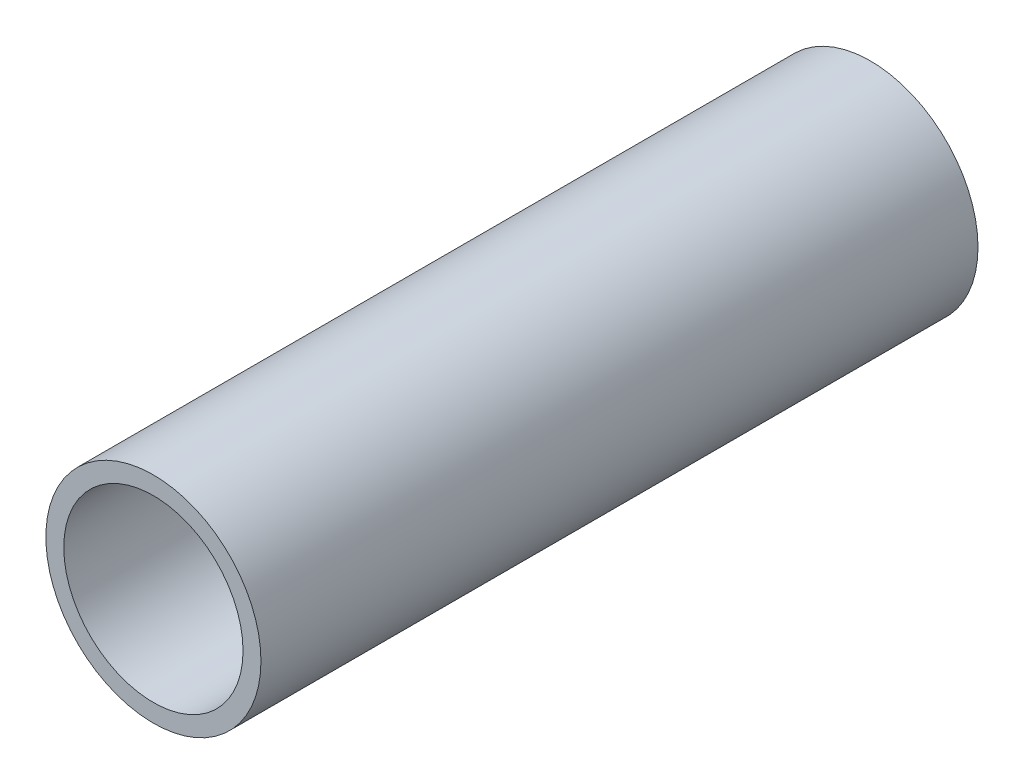
SolidWorks part; units mm, degrees
ref_plane "前视基准面" through (0, 0, 0) normal (0, 0, 1) x (1, 0, 0)
ref_plane "上视基准面" through (0, 0, 0) normal (0, 1, 0) x (1, 0, 0)
ref_plane "右视基准面" through (0, 0, 0) normal (1, 0, 0) x (0, 0, -1)
other "Configuration Table"
sketch "Profile1" plane through (0, 0, 0) normal (0, 0, 1) x (1, 0, 0)
  circle A0 centre (0, 0) radius 5
sketch "Path1" plane through (0, 0, 0) normal (1, 0, 0) x (0, 0, -1)
  line L0 (0, 0) -> (-40, 0)
sweep "sweep_thin_one_dir_t1" add profiles "Profile1" path "Path1" parameters "D1"=1
